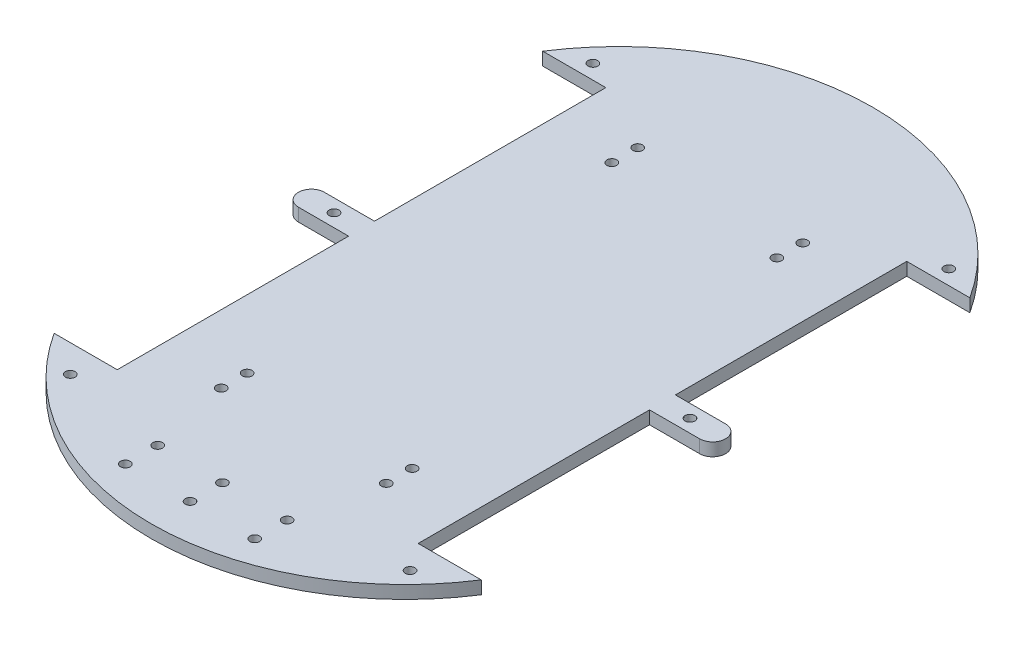
SolidWorks part; units mm, degrees
material "Acrylic (Medium-high impact)"
ref_plane "Front Plane" through (0, 0, 0) normal (0, 0, 1) x (1, 0, 0)
ref_plane "Top Plane" through (0, 0, 0) normal (0, 1, 0) x (1, 0, 0)
ref_plane "Right Plane" through (0, 0, 0) normal (1, 0, 0) x (0, 0, -1)
sketch "Sketch1" plane through (0, 0, 0) normal (0, 1, 0) x (1, 0, 0)
  line L0 (-62, 0) -> (62, 0) construction
  line L1 (-46.5, 0) -> (46.5, 0) construction
  line L2 (46.5, -4) -> (46.5, 4) construction
  line L3 (62, 4) -> (46.5, 4)
  line L4 (46.5, 4) -> (46.5, 75.5)
  line L5 (46.5, 75.5) -> (66, 75.5)
  line L6 (0, -111.5) -> (0, 111.5) construction
  line L7 (-46.5, -4) -> (-46.5, 4) construction
  line L8 (-46.5, 75.5) -> (-66, 75.5)
  line L9 (-46.5, 4) -> (-46.5, 75.5)
  line L10 (-62, 4) -> (-46.5, 4)
  line L11 (-62, -4) -> (-46.5, -4)
  line L12 (-46.5, -4) -> (-46.5, -75.5)
  line L13 (-46.5, -75.5) -> (-66, -75.5)
  line L14 (46.5, -75.5) -> (66, -75.5)
  line L15 (46.5, -4) -> (46.5, -75.5)
  line L16 (62, -4) -> (46.5, -4)
  arc A0 (62, 4) -> (62, -4) centre (62, 0) cw
  arc A1 (66, 75.5) -> (-66, 75.5) centre (0, 33) ccw
  arc A2 (-62, 4) -> (-62, -4) centre (-62, 0) ccw
  arc A3 (66, -75.5) -> (-66, -75.5) centre (0, -33) cw
  point P4 (0, 0)
  point P13 (66, 0)
  point P23 (0, 0)
  dimension "D4" = 71.5
  dimension "D3" = 4
  dimension "D7" = 78.5
  dimension "D1" = 66
  dimension "D2" = 46.5
  dimension "D5" = 36
  dimension "D6" = 66
extrude "Plate" add sketch "Sketch1" along normal blind 4
sketch "Sketch2" plane through (0, 4, 0) normal (0, 1, 0) x (1, 0, 0)
  line L0 (0, 0) -> (55, 0) construction
  line L1 (0, 0) -> (0, 80) construction
  line L2 (0, 80) -> (55, 80) construction
  line L3 (46.5, 75.5) -> (66, 75.5) construction
  line L4 (46.5, 4) -> (46.5, 75.5) construction
  line L7 (66, -75.5) -> (46.5, -75.5) construction
  line L8 (46.5, -75.5) -> (46.5, -4) construction
  circle A0 centre (55, 0) radius 1.5
  circle A1 centre (55, 80) radius 1.5
  circle A2 centre (-55, 0) radius 1.5
  circle A3 centre (-55, 80) radius 1.5
  circle A4 centre (52.5, -84) radius 1.5
  circle A5 centre (-52.5, -84) radius 1.5
  dimension "D3" = 1.5
  dimension "D5" = 3
  dimension "D1" = 8.5
  dimension "D2" = 4.5
  dimension "D4" = 8.5
  dimension "D6" = 8.5
  dimension "D7" = 6
extrude "Plate mountings" cut sketch "Sketch2" against normal through all
sketch "Sketch3" plane through (0, 4, 0) normal (0, 1, 0) x (1, 0, 0)
  line L0 (0, 0) -> (0, -89.5) construction
  line L1 (-20, -89.5) -> (0, -89.5) construction
  line L2 (0, -89.5) -> (-20, -89.5) construction
  circle A0 centre (-20, -89.5) radius 1.5
  circle A1 centre (0, -89.5) radius 1.5
  circle A2 centre (20, -89.5) radius 1.5
  circle A3 centre (0, -99.5) radius 1.5
  circle A4 centre (20, -99.5) radius 1.5
  circle A5 centre (-20, -99.5) radius 1.5
  dimension "D3" = 2
  dimension "D2" = 3
  dimension "D1" = 20
  dimension "D4" = 20
  dimension "D5" = 89.5
  dimension "D6" = 10
  dimension "D8" = 20
extrude "Light sensor" cut sketch "Sketch3" against normal through all
sketch "Sketch4" plane through (0, 4, 0) normal (0, 1, 0) x (1, 0, 0)
  line L0 (46.5, 75.5) -> (19.0125, 75.5) construction
  line L1 (25.5, 56.35) -> (25.5, 64.35) construction
  line L2 (25.5, 60.35) -> (25.5, 39.75) construction
  line L3 (46.5, 39.75) -> (25.5, 39.75) construction
  line L4 (46.5, 4) -> (46.5, 75.5) construction
  circle A0 centre (25.5, 64.35) radius 1.5
  circle A1 centre (25.5, 56.35) radius 1.5
  point P3 (25.5, 60.35)
  dimension "D2" = 3
  dimension "D4" = 3
  dimension "D1" = 21
  dimension "D3" = 20.6
  dimension "D5" = 8
  dimension "D6" = 12.9
extrude "Cut-Extrude3" cut sketch "Sketch4" against normal through all
mirror "Mirror1" about plane through (0, 0, 0) normal (1, 0, 0) of "Cut-Extrude3"
mirror "Mirror2" about plane through (0, 0, 0) normal (0, 0, 1) of "Mirror1", "Cut-Extrude3"
